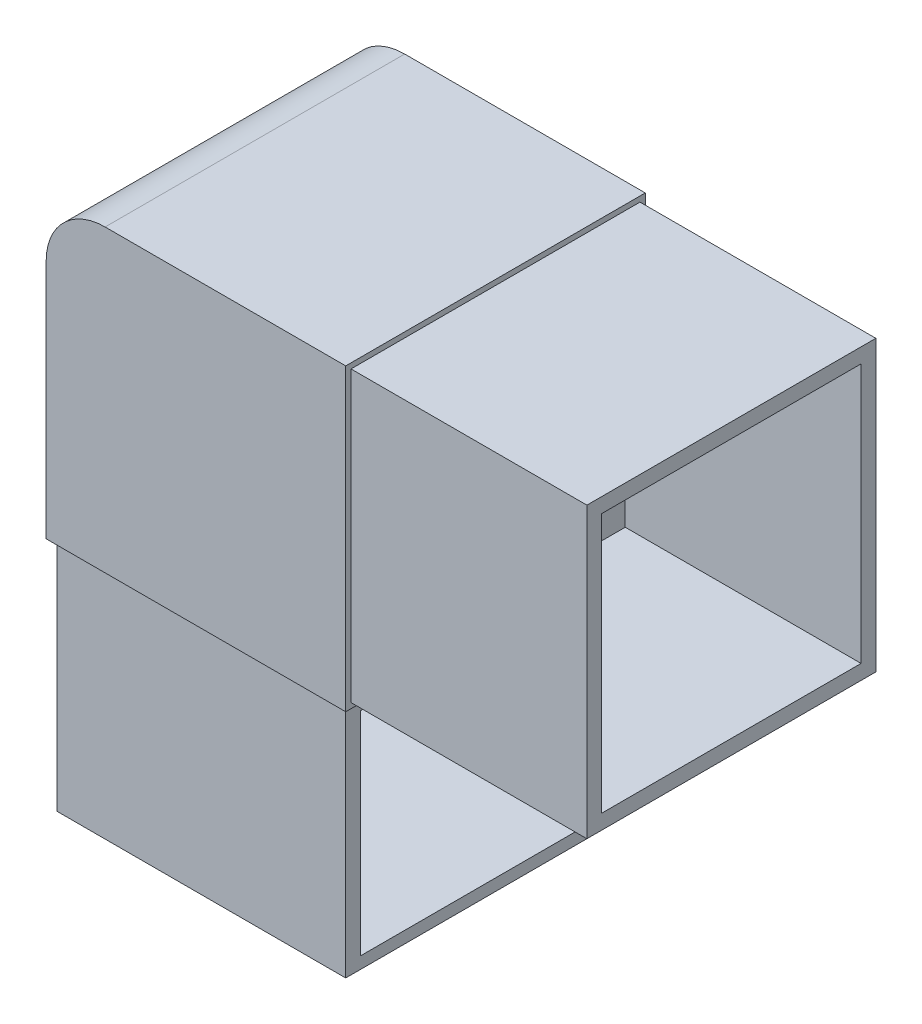
SolidWorks part; units mm, degrees
ref_plane "Front Plane" through (0, 0, 0) normal (0, 0, 1) x (1, 0, 0)
ref_plane "Top Plane" through (0, 0, 0) normal (0, 1, 0) x (1, 0, 0)
ref_plane "Right Plane" through (0, 0, 0) normal (1, 0, 0) x (0, 0, -1)
sketch "Sketch1" plane through (0, 0, 0) normal (0, 1, 0) x (1, 0, 0)
  line L1 (-12.7, 12.7) -> (12.7, 12.7)
  line L2 (-12.7, 12.7) -> (-12.7, -12.7)
  line L3 (-12.7, -12.7) -> (12.7, -12.7)
  line L4 (12.7, 12.7) -> (12.7, -12.7)
  line L5 (-12.7, 12.7) -> (12.7, -12.7) construction
  line L6 (-12.7, -12.7) -> (12.7, 12.7) construction
  point P0 (0, 0)
extrude "Boss-Extrude1" add sketch "Sketch1" along normal blind 25.4
fillet "Fillet1" radius 5 1 edges at (-12.7, 25.4, 0)
sketch "Sketch2" plane through (12.7, 0, 0) normal (1, 0, 0) x (0, 0, -1)
  line L0 (0, 25.4) -> (0, 24.95)
  line L1 (-12.7, 25.4) -> (12.7, 25.4) construction
  line L2 (0, 0.45) -> (0, 0)
  line L3 (-12.25, 24.95) -> (12.25, 24.95)
  line L4 (-12.25, 24.95) -> (-12.25, 0.45)
  line L5 (-12.25, 0.45) -> (12.25, 0.45)
  line L6 (12.25, 24.95) -> (12.25, 0.45)
  point P5 (0, 12.7)
extrude "Boss-Extrude2" add sketch "Sketch2" along normal blind 20 contours L6 L3 L4 L5
sketch "Sketch3" plane through (32.7, 0, 0) normal (1, 0, 0) x (0, 0, -1)
  line L4 (-11, 23.7) -> (11, 23.7)
  line L5 (-11, 23.7) -> (-11, 1.7)
  line L6 (-11, 1.7) -> (11, 1.7)
  line L7 (11, 23.7) -> (11, 1.7)
  point P6 (0, 12.7)
extrude "Cut-Extrude1" cut sketch "Sketch3" against normal blind 20
sketch "Sketch4" plane through (0, 0, 0) normal (0, -1, 0) x (1, 0, 0)
  line L1 (-12.25, 12.25) -> (12.25, 12.25)
  line L2 (-12.25, 12.25) -> (-12.25, -12.25)
  line L3 (-12.25, -12.25) -> (12.25, -12.25)
  line L4 (12.25, 12.25) -> (12.25, -12.25)
  line L5 (-12.25, 12.25) -> (12.25, -12.25) construction
  line L6 (-12.25, -12.25) -> (12.25, 12.25) construction
  point P0 (0, 0)
extrude "Boss-Extrude3" add sketch "Sketch4" along normal blind 20
sketch "Sketch5" plane through (12.25, 0, 0) normal (1, 0, 0) x (0, 0, -1)
  line L3 (-11, -1) -> (11, -1)
  line L4 (-11, -1) -> (-11, -19)
  line L5 (-11, -19) -> (11, -19)
  line L6 (11, -1) -> (11, -19)
  point P5 (0, -10)
extrude "Cut-Extrude2" cut sketch "Sketch5" against normal blind 23
